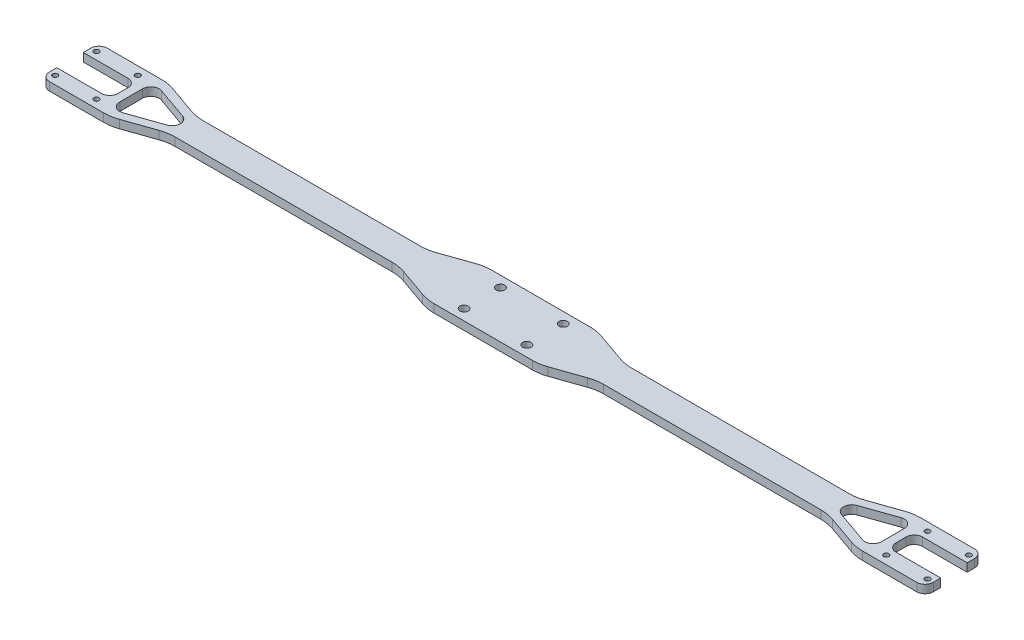
SolidWorks part; units mm, degrees
ref_plane "Alzado" through (0, 0, 0) normal (0, 0, 1) x (1, 0, 0)
ref_plane "Planta" through (0, 0, 0) normal (0, 1, 0) x (1, 0, 0)
ref_plane "Vista lateral" through (0, 0, 0) normal (1, 0, 0) x (0, 0, -1)
sketch "Croquis2" plane through (0, 0, 0) normal (0, 1, 0) x (1, 0, 0)
  line L0 (-267.5, 8) -> (-235.5, 8)
  line L1 (-267.5, -17.5) -> (-225.5, -17.5)
  line L2 (-267.5, -17.5) -> (-267.5, -8)
  line L3 (-267.5, 17.5) -> (-225.5, 17.5)
  line L4 (267.5, -17.5) -> (267.5, -8)
  line L5 (-267.5, -17.5) -> (267.5, 17.5) construction
  line L6 (-267.5, 17.5) -> (267.5, -17.5) construction
  line L7 (-235.5, 8) -> (-235.5, -8)
  line L8 (-235.5, -8) -> (-267.5, -8)
  line L9 (-267.5, 8) -> (-267.5, 17.5)
  line L10 (0, -44.3823) -> (0, 46.8097) construction
  line L11 (-225.5, 17.5) -> (-199.75, 8.5)
  line L12 (-199.75, 8.5) -> (-59.75, 8.5)
  line L13 (-59.75, 8.5) -> (-34, 17.5)
  line L14 (-45.6715, 0) -> (41.3126, 0) construction
  line L15 (-34, 17.5) -> (34, 17.5)
  line L16 (59.75, 8.5) -> (34, 17.5)
  line L17 (199.75, 8.5) -> (59.75, 8.5)
  line L18 (225.5, 17.5) -> (199.75, 8.5)
  line L19 (225.5, 17.5) -> (267.5, 17.5)
  line L20 (225.5, -17.5) -> (199.75, -8.5)
  line L21 (199.75, -8.5) -> (59.75, -8.5)
  line L22 (59.75, -8.5) -> (34, -17.5)
  line L23 (-225.5, -17.5) -> (-199.75, -8.5)
  line L24 (-59.75, -8.5) -> (-34, -17.5)
  line L25 (-199.75, -8.5) -> (-59.75, -8.5)
  line L26 (-34, -17.5) -> (34, -17.5)
  line L27 (225.5, -17.5) -> (267.5, -17.5)
  line L28 (235.5, -8) -> (267.5, -8)
  line L29 (235.5, 8) -> (235.5, -8)
  line L30 (267.5, 8) -> (235.5, 8)
  line L31 (267.5, 8) -> (267.5, 17.5)
  line L32 (-204.0263, 4.698) -> (-223.8503, 11.6268)
  line L33 (-204.0263, -4.698) -> (-223.8503, -11.6268)
  line L34 (-230.5, 6.9068) -> (-230.5, -6.9068)
  line L35 (204.0263, 4.698) -> (223.8503, 11.6268)
  line L36 (230.5, 6.9068) -> (230.5, -6.9068)
  line L37 (204.0263, -4.698) -> (223.8503, -11.6268)
  arc A1 (-230.5, -6.9068) -> (-223.8503, -11.6268) centre (-225.5, -6.9068) ccw
  arc A3 (-223.8503, 11.6268) -> (-230.5, 6.9068) centre (-225.5, 6.9068) ccw
  arc A4 (-204.0263, -4.698) -> (-204.0263, 4.698) centre (-205.7376, 0) ccw
  arc A5 (204.0263, -4.698) -> (204.0263, 4.698) centre (205.7376, 0) cw
  arc A6 (223.8503, 11.6268) -> (230.5, 6.9068) centre (225.5, 6.9068) cw
  arc A7 (230.5, -6.9068) -> (223.8503, -11.6268) centre (225.5, -6.9068) cw
  point P0 (0, 0)
  dimension "D12" = 5
  dimension "D15" = 5
  dimension "D16" = 5
  dimension "D17" = 5
  dimension "D1" = 535
  dimension "D2" = 35
  dimension "D3" = 9.5
  dimension "D4" = 9.5
  dimension "D5" = 32
  dimension "D6" = 8.5
  dimension "D7" = 10
  dimension "D8" = 34
  dimension "D9" = 25.75
  dimension "D10" = 140
  dimension "D11" = 25.75
  dimension "D13" = 5
  dimension "D14" = 5
  dimension "D18" = 21
  dimension "D19" = 21
extrude "Saliente-Extruir1" add sketch "Croquis2" along normal blind 5
fillet "Redondeo1" radius 5 8 edges at (-267.5, 2.5, 17.5) (-267.5, 2.5, -17.5) (-235.5, 2.5, 8) (-235.5, 2.5, -8) (235.5, 2.5, -8) (235.5, 2.5, 8) (267.5, 2.5, -17.5) (267.5, 2.5, 17.5)
sketch "Croquis3" plane through (0, 5, 0) normal (0, 1, 0) x (1, 0, 0)
  line L1 (-225.5, 17.5) -> (-262.5, 17.5) construction
  line L3 (0, -23.5049) -> (0, 30.5256) construction
  line L6 (29.2999, 0) -> (-39.5666, 0) construction
  line L7 (-267.5, -8) -> (-267.5, -12.5) construction
  circle A0 centre (-264, -12.5) radius 1.55
  circle A1 centre (-239, -12.5) radius 1.55
  circle A2 centre (-239, 12.5) radius 1.55
  circle A3 centre (-264, 12.5) radius 1.55
  circle A4 centre (264, 12.5) radius 1.55
  circle A5 centre (239, 12.5) radius 1.55
  circle A6 centre (239, -12.5) radius 1.55
  circle A7 centre (264, -12.5) radius 1.55
  circle A8 centre (-18, -11) radius 2.55
  circle A9 centre (20, -11) radius 2.55
  circle A10 centre (20, 11) radius 2.55
  circle A11 centre (-18, 11) radius 2.55
  dimension "D1" = 3.1
  dimension "D4" = 25
  dimension "D5" = 25
  dimension "D7" = 3.5
  dimension "D8" = 5.1
  dimension "D12" = 11
  dimension "D6" = 5
  dimension "D11" = 18
  dimension "D2" = 2
  dimension "D3" = 2
  dimension "D9" = 2
  dimension "D10" = 2
extrude "Cortar-Extruir1" cut sketch "Croquis3" against normal through all
fillet "Redondeo3" radius 25 16 edges at (-225.5, 2.5, 17.5) (-225.5, 2.5, -17.5) (-199.75, 2.5, -8.5) (-199.75, 2.5, 8.5) (199.75, 2.5, 8.5) (225.5, 2.5, 17.5) (225.5, 2.5, -17.5) (199.75, 2.5, -8.5) (59.75, 2.5, -8.5) (34, 2.5, -17.5) (-34, 2.5, -17.5) (-59.75, 2.5, -8.5) (59.75, 2.5, 8.5) (34, 2.5, 17.5) (-34, 2.5, 17.5) (-59.75, 2.5, 8.5)
